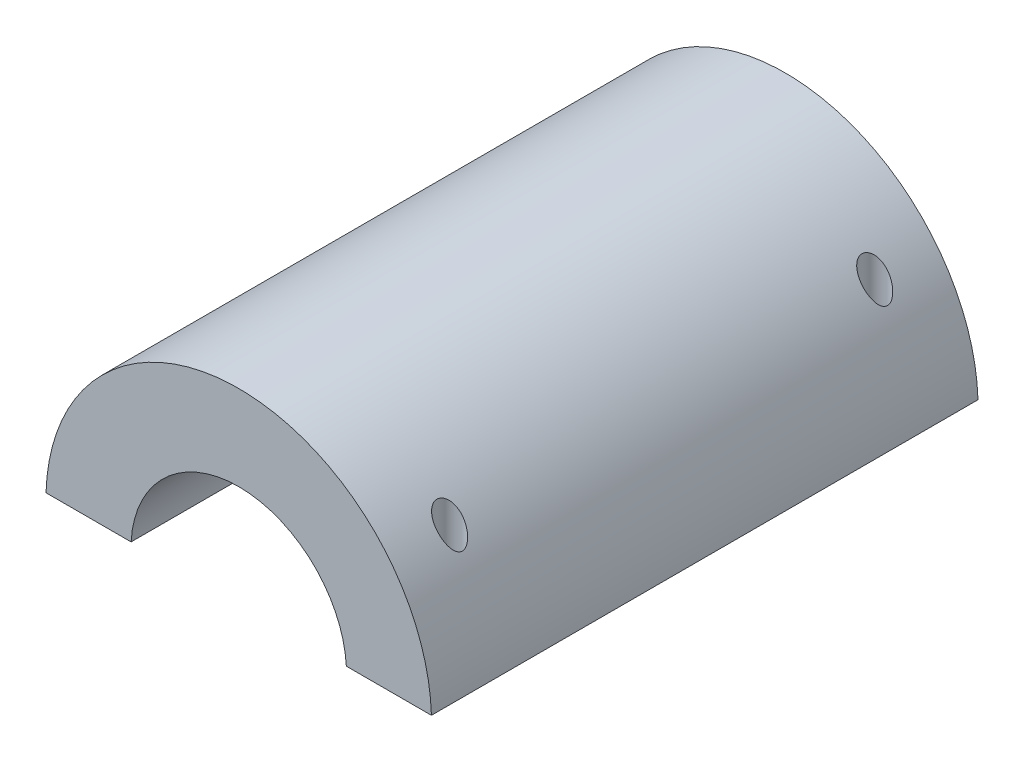
SolidWorks part; units mm, degrees
ref_plane "Front" through (0, 0, 0) normal (0, 0, 1) x (1, 0, 0)
ref_plane "Top" through (0, 0, 0) normal (0, 1, 0) x (1, 0, 0)
ref_plane "Right" through (0, 0, 0) normal (1, 0, 0) x (0, 0, -1)
sketch "Sketch1" plane through (0, 0, 0) normal (0, 0, 1) x (1, 0, 0)
  line L0 (-31.75, 0) -> (31.75, 0) construction
  line L1 (-31.7342, 1) -> (-17.7218, 1)
  line L2 (-31.75, 1) -> (31.75, 1) construction
  line L3 (17.7218, 1) -> (31.7342, 1)
  arc A0 (31.7342, 1) -> (-31.7342, 1) centre (0, 0) ccw
  arc A1 (17.7218, 1) -> (-17.7218, 1) centre (0, 0) ccw
  dimension "D1" = 35.5
  dimension "D2" = 63.5
  dimension "D3" = 1
extrude "Boss-Extrude1" add sketch "Sketch1" along normal blind 90
sketch "Sketch2" plane through (0, 1, 0) normal (0, -1, 0) x (-1, 0, 0)
  line L0 (24.728, -90) -> (24.728, 0) construction
  line L1 (31.7342, -90) -> (17.7218, -90) construction
  line L2 (31.7342, 0) -> (17.7218, 0) construction
  line L3 (-24.728, -90) -> (-24.728, 0) construction
  line L4 (-17.7218, -90) -> (-31.7342, -90) construction
  line L5 (-17.7218, 0) -> (-31.7342, 0) construction
  line L6 (0, -90) -> (0, 0) construction
  line L7 (-17.7218, -90) -> (17.7218, -90) construction
  circle A0 centre (24.728, -80) radius 1
  circle A1 centre (24.728, -10) radius 1
  circle A2 centre (-24.728, -10) radius 1
  circle A3 centre (-24.728, -80) radius 1
  dimension "D1" = 10
  dimension "D2" = 10
  dimension "D3" = 2
hole_wizard "Tap Drill for M5x0.8 Tap1" positions "3DSketch1" profile "Sketch3" hole size "M5x0.8" standard "ANSI Metric" end condition up to next
sketch3d "3DSketch1"
  point P0 (-24.728, 1, 80)
  point P3 (-24.728, 1, 10)
  point P6 (24.728, 1, 80)
  point P9 (24.728, 1, 10)
sketch "Sketch3" plane through (-24.728, 1, 80) normal (1, 0, 0) x (0, 0, -1)
  line L0 (0, 0) -> (0, 18.9145)
  line L1 (0, 18.9145) -> (2.1, 18.9145)
  line L2 (2.1, 18.9145) -> (2.1, 0)
  line L5 (2.1, 0) -> (0, 0)
  line L11 (0, -6.35) -> (0, 107.95) construction
  dimension "Thru Hole Dia." = 4.2
  dimension "Thru Hole Depth" = 18.9145
